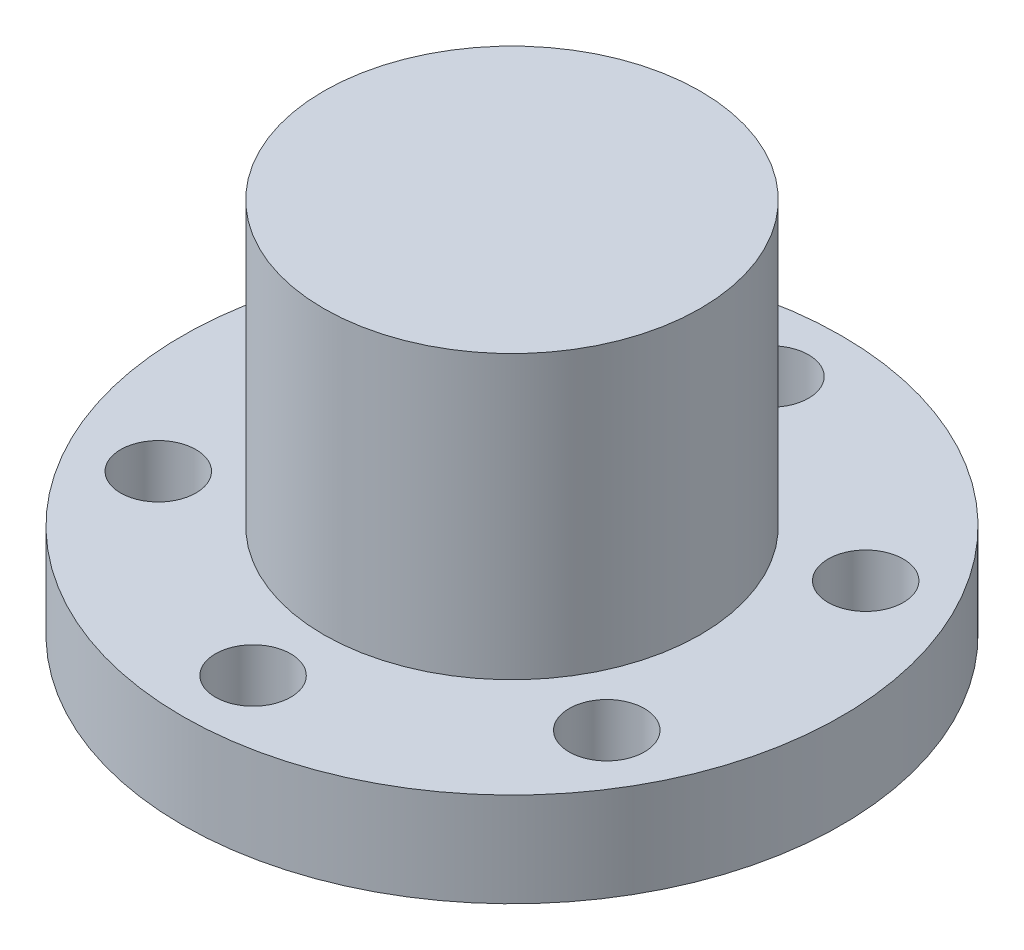
SolidWorks part; units mm, degrees
ref_plane "Front Plane" through (0, 0, 0) normal (0, 0, 1) x (1, 0, 0)
ref_plane "Top Plane" through (0, 0, 0) normal (0, 1, 0) x (1, 0, 0)
ref_plane "Right Plane" through (0, 0, 0) normal (1, 0, 0) x (0, 0, -1)
sketch "Sketch2" plane through (0, 0, 0) normal (0, 1, 0) x (1, 0, 0)
  circle A0 centre (0, 0) radius 17.5
  circle A1 centre (0, 0) radius 13.75 construction
  circle A2 centre (0, 13.75) radius 2
  circle A3 centre (11.9078, 6.875) radius 2
  circle A4 centre (11.9078, -6.875) radius 2
  circle A5 centre (0, -13.75) radius 2
  circle A6 centre (-11.9078, -6.875) radius 2
  circle A7 centre (-11.9078, 6.875) radius 2
  point P7 (0, 0)
  point P8 (0, 0)
  point P18 (0, 0)
  dimension "D1" = 35
  dimension "D2" = 27.5
  dimension "D3" = 4
  dimension "D4" = 6
extrude "Boss-Extrude1" add sketch "Sketch2" along normal blind 5
sketch "Sketch3" plane through (0, 5, 0) normal (0, 1, 0) x (1, 0, 0)
  circle A0 centre (0, 0) radius 10
  dimension "D1" = 20
extrude "Boss-Extrude2" add sketch "Sketch3" along normal blind 15
